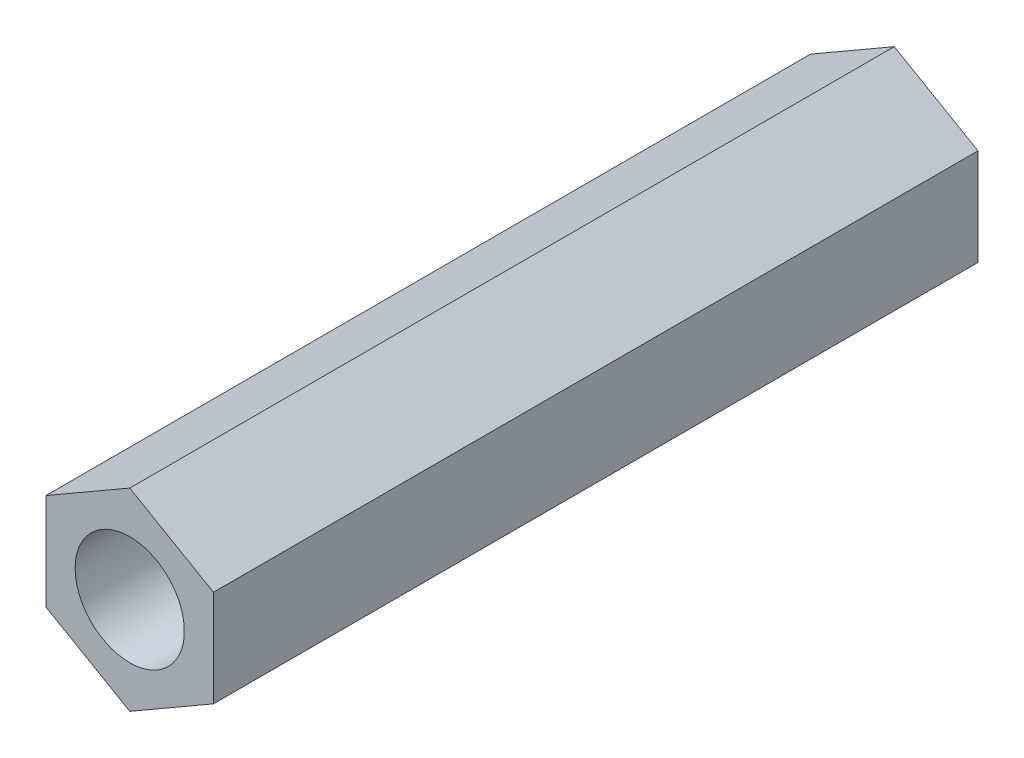
SolidWorks part; units mm, degrees
material "黄铜"
ref_plane "前视基准面" through (0, 0, 0) normal (0, 0, 1) x (1, 0, 0)
ref_plane "上视基准面" through (0, 0, 0) normal (0, 1, 0) x (1, 0, 0)
ref_plane "右视基准面" through (0, 0, 0) normal (1, 0, 0) x (0, 0, -1)
other "Configuration Table"
sketch "草图1" plane through (0, 0, 0) normal (0, 0, 1) x (1, 0, 0)
  line L1 (2.3, -1.3279) -> (2.3, 1.3279)
  line L2 (2.3, 1.3279) -> (0, 2.6558)
  line L3 (0, 2.6558) -> (-2.3, 1.3279)
  line L4 (-2.3, 1.3279) -> (-2.3, -1.3279)
  line L5 (-2.3, -1.3279) -> (0, -2.6558)
  line L6 (0, -2.6558) -> (2.3, -1.3279)
  circle A0 centre (0, 0) radius 2.3 construction
  circle A1 centre (0, 0) radius 1.5
  dimension "D2" = 3
  dimension "D1" = 4.6
extrude "凸台-拉伸1" add sketch "草图1" along normal blind 21
